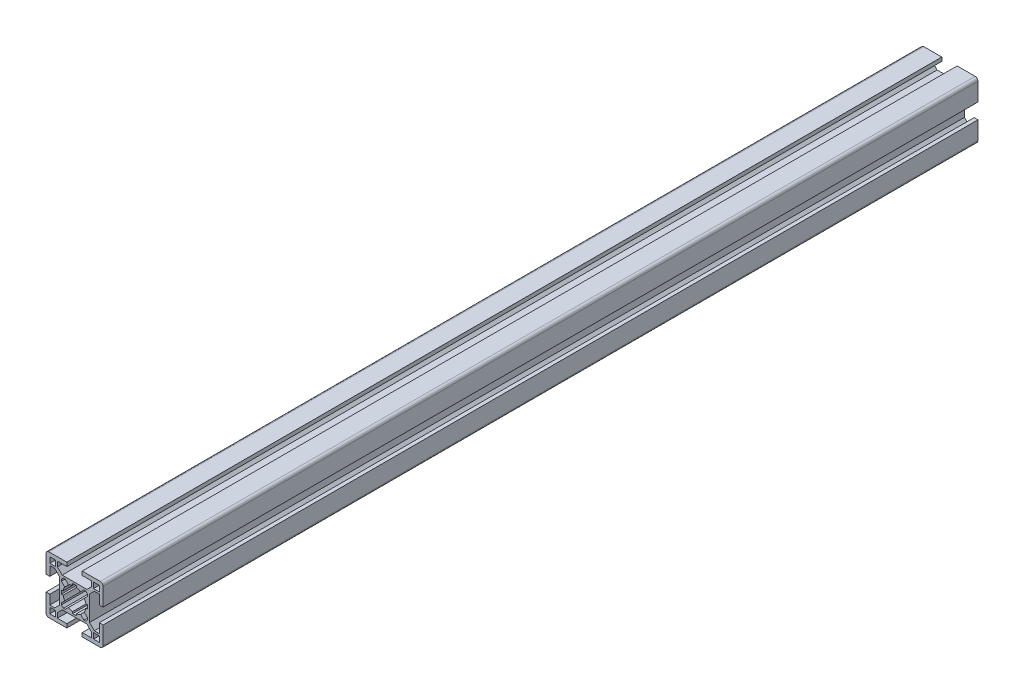
SolidWorks part; units mm, degrees
material "6063-T5"
ref_plane "Plano frontal" through (0, 0, 0) normal (0, 0, 1) x (1, 0, 0)
ref_plane "Plano superior" through (0, 0, 0) normal (0, 1, 0) x (1, 0, 0)
ref_plane "Plano direito" through (0, 0, 0) normal (1, 0, 0) x (0, 0, -1)
sketch "Esboço1" plane through (0, 0, 0) normal (0, 0, 1) x (1, 0, 0)
  line L0 (15, 13.5) -> (15, 4.05)
  line L1 (-13.5, 15) -> (-4.05, 15)
  line L8 (-9, 13) -> (-9, 10.4142)
  line L9 (-10, 13) -> (-10, 10)
  line L10 (-9, 13) -> (-4.05, 13)
  line L11 (-6.9, 1) -> (-6.9, 0)
  line L12 (-13, 13) -> (-10, 13)
  line L13 (-10.4142, 9) -> (-7.9, 6.4858)
  line L14 (-6.9, 1) -> (-5.9668, 1)
  line L15 (-15, 4.05) -> (-13, 4.05)
  line L16 (-6.4858, 7.9) -> (0, 7.9)
  line L17 (-4.9126, 6.9) -> (-3.1673, 5.1547)
  line L18 (-5.8279, 6.9) -> (-4.9126, 6.9)
  line L19 (-6.9, 5.8279) -> (-6.9, 4.9126)
  line L20 (-4.05, 15) -> (-4.05, 13)
  line L21 (13, 9) -> (10.4142, 9)
  line L22 (-1, 6.9) -> (-1, 5.9668)
  line L23 (-6.9, 4.9126) -> (-5.1547, 3.1673)
  line L24 (-5.8279, 6.9) -> (-6.9, 5.8279)
  line L25 (-7.9, 6.4858) -> (-7.9, 0)
  line L26 (13, 10) -> (10, 10)
  line L27 (-9, 10.4142) -> (-6.4858, 7.9)
  line L28 (13, 9) -> (13, 4.05)
  line L29 (-1, 6.9) -> (0, 6.9)
  line L30 (-6.4858, 6.9) -> (0, 6.9) construction
  line L31 (-13, 13) -> (-13, 10)
  line L32 (-13, 9) -> (-13, 4.05)
  line L33 (-15, 15) -> (-15, -15) construction
  line L34 (-15, 15) -> (15, 15) construction
  line L35 (-13, 10) -> (-10, 10)
  line L36 (-13, 9) -> (-10.4142, 9)
  line L37 (-13, 13) -> (13, 13) construction
  line L38 (-15, 13.5) -> (-15, 4.05)
  line L39 (1, 6.9) -> (0, 6.9)
  line L40 (13, 13) -> (13, 10)
  line L41 (-13, 13) -> (-13, -13) construction
  line L42 (9, 10.4142) -> (6.4858, 7.9)
  line L43 (1, 6.9) -> (1, 5.9668)
  line L44 (4.05, 15) -> (4.05, 13)
  line L45 (7.9, 6.4858) -> (7.9, 0)
  line L46 (6.9, 4.9126) -> (5.1547, 3.1673)
  line L47 (6.9, 5.8279) -> (6.9, 4.9126)
  line L48 (5.8279, 6.9) -> (4.9126, 6.9)
  line L49 (-7.9, 7.9) -> (7.9, 7.9) construction
  line L50 (15, 4.05) -> (13, 4.05)
  line L51 (6.9, 1) -> (5.9668, 1)
  line L52 (4.9126, 6.9) -> (3.1673, 5.1547)
  line L53 (6.9, 5.8279) -> (5.8279, 6.9)
  line L54 (6.4858, 7.9) -> (0, 7.9)
  line L55 (10.4142, 9) -> (7.9, 6.4858)
  line L56 (6.9, 1) -> (6.9, 0)
  line L57 (13, 13) -> (10, 13)
  line L58 (9, 13) -> (4.05, 13)
  line L59 (10, 13) -> (10, 10)
  line L60 (9, 13) -> (9, 10.4142)
  line L61 (13.5, 15) -> (4.05, 15)
  line L62 (13.5, -15) -> (4.05, -15)
  line L63 (9, -13) -> (9, -10.4142)
  line L64 (10, -13) -> (10, -10)
  line L65 (9, -13) -> (4.05, -13)
  line L66 (-7.9, 7.9) -> (-7.9, -7.9) construction
  line L67 (6.9, -1) -> (6.9, 0)
  line L68 (-15, -15) -> (15, -15) construction
  line L69 (15, 15) -> (15, -15) construction
  line L70 (13, 13) -> (13, -13) construction
  line L71 (-13, -13) -> (13, -13) construction
  line L72 (7.9, 7.9) -> (7.9, -7.9) construction
  line L73 (-7.9, -7.9) -> (7.9, -7.9) construction
  line L74 (13, -13) -> (10, -13)
  line L75 (10.4142, -9) -> (7.9, -6.4858)
  line L76 (6.9, -1) -> (5.9668, -1)
  line L77 (15, -4.05) -> (13, -4.05)
  line L78 (6.4858, -7.9) -> (0, -7.9)
  line L79 (4.9126, -6.9) -> (3.1673, -5.1547)
  line L80 (5.8279, -6.9) -> (4.9126, -6.9)
  line L81 (6.9, -5.8279) -> (6.9, -4.9126)
  line L82 (4.05, -15) -> (4.05, -13)
  line L83 (1, -6.9) -> (1, -5.9668)
  line L84 (6.9, -4.9126) -> (5.1547, -3.1673)
  line L85 (5.8279, -6.9) -> (6.9, -5.8279)
  line L86 (7.9, -6.4858) -> (7.9, 0)
  line L87 (9, -10.4142) -> (6.4858, -7.9)
  line L88 (1, -6.9) -> (0, -6.9)
  line L89 (13, -13) -> (13, -10)
  line L90 (13, -9) -> (13, -4.05)
  line L91 (13, -10) -> (10, -10)
  line L92 (13, -9) -> (10.4142, -9)
  line L93 (15, -13.5) -> (15, -4.05)
  line L94 (-15, -13.5) -> (-15, -4.05)
  line L95 (-13, -9) -> (-10.4142, -9)
  line L96 (-13, -10) -> (-10, -10)
  line L97 (-13, -9) -> (-13, -4.05)
  line L98 (-1, -6.9) -> (0, -6.9)
  line L99 (-13, -13) -> (-13, -10)
  line L100 (-9, -10.4142) -> (-6.4858, -7.9)
  line L101 (-1, -6.9) -> (-1, -5.9668)
  line L102 (-4.05, -15) -> (-4.05, -13)
  line L103 (-7.9, -6.4858) -> (-7.9, 0)
  line L104 (-6.9, -4.9126) -> (-5.1547, -3.1673)
  line L105 (-6.9, -5.8279) -> (-6.9, -4.9126)
  line L106 (-5.8279, -6.9) -> (-4.9126, -6.9)
  line L107 (-15, -4.05) -> (-13, -4.05)
  line L108 (-6.9, -1) -> (-5.9668, -1)
  line L109 (-4.9126, -6.9) -> (-3.1673, -5.1547)
  line L110 (-6.9, -5.8279) -> (-5.8279, -6.9)
  line L111 (-6.4858, -7.9) -> (0, -7.9)
  line L112 (-10.4142, -9) -> (-7.9, -6.4858)
  line L113 (-6.9, -1) -> (-6.9, 0)
  line L114 (-13, -13) -> (-10, -13)
  line L115 (-9, -13) -> (-4.05, -13)
  line L116 (-10, -13) -> (-10, -10)
  line L117 (-9, -13) -> (-9, -10.4142)
  line L118 (-13.5, -15) -> (-4.05, -15)
  arc A0 (-1, 5.9668) -> (-3.1673, 5.1547) centre (0, 0) ccw
  arc A1 (-5.9668, 1) -> (-5.1547, 3.1673) centre (0, 0) cw
  arc A2 (-13.5, 15) -> (-15, 13.5) centre (-13.5, 13.5) ccw
  arc A3 (5.9668, 1) -> (5.1547, 3.1673) centre (0, 0) ccw
  arc A4 (1, 5.9668) -> (3.1673, 5.1547) centre (0, 0) cw
  arc A5 (15, 13.5) -> (13.5, 15) centre (13.5, 13.5) ccw
  arc A6 (1, -5.9668) -> (3.1673, -5.1547) centre (0, 0) ccw
  arc A7 (5.9668, -1) -> (5.1547, -3.1673) centre (0, 0) cw
  arc A8 (13.5, -15) -> (15, -13.5) centre (13.5, -13.5) ccw
  arc A9 (-5.9668, -1) -> (-5.1547, -3.1673) centre (0, 0) ccw
  arc A10 (-1, -5.9668) -> (-3.1673, -5.1547) centre (0, 0) cw
  arc A11 (-15, -13.5) -> (-13.5, -15) centre (-13.5, -13.5) ccw
  point P139 (0, 0)
  dimension "D1" = 4
extrude "Ressalto-extrusão1" add sketch "Esboço1" along normal mid plane 460
